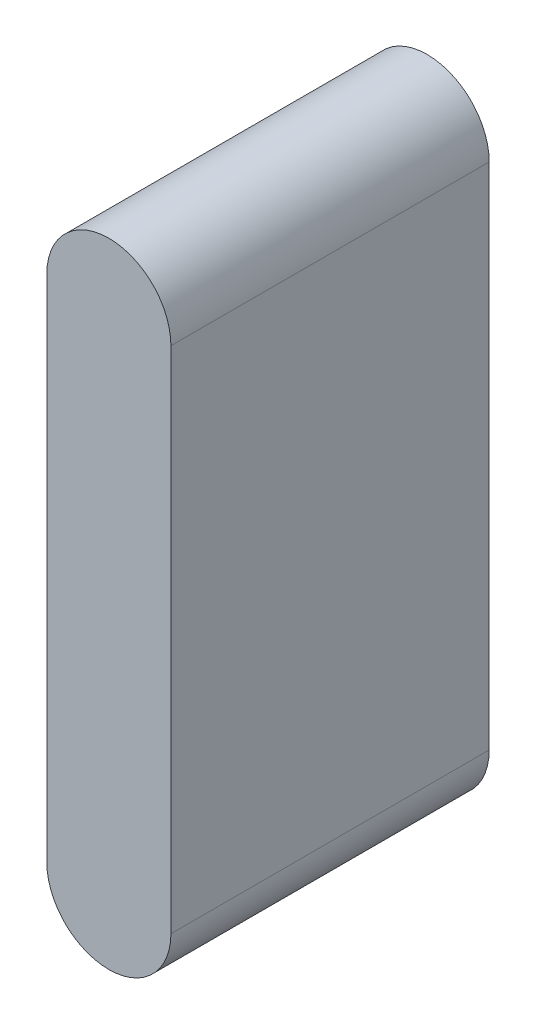
SolidWorks part; units mm, degrees
ref_plane "前视基准面" through (0, 0, 0) normal (0, 0, 1) x (1, 0, 0)
ref_plane "上视基准面" through (0, 0, 0) normal (0, 1, 0) x (1, 0, 0)
ref_plane "右视基准面" through (0, 0, 0) normal (1, 0, 0) x (0, 0, -1)
other "Configuration Table"
sketch "草图1" plane through (0, 0, 0) normal (0, 0, 1) x (1, 0, 0)
  line L0 (0, 9.5411) -> (0, -6.4589) construction
  line L1 (1.95, 9.5411) -> (1.95, -6.4589)
  line L2 (-1.95, 9.5411) -> (-1.95, -6.4589)
  arc A0 (1.95, 9.5411) -> (-1.95, 9.5411) centre (0, 9.5411) ccw
  arc A1 (-1.95, -6.4589) -> (1.95, -6.4589) centre (0, -6.4589) ccw
  point P3 (0, 1.5411)
  dimension "D1" = 1.95
  dimension "D2" = 16
extrude "凸台-拉伸1" add sketch "草图1" along normal blind 10
